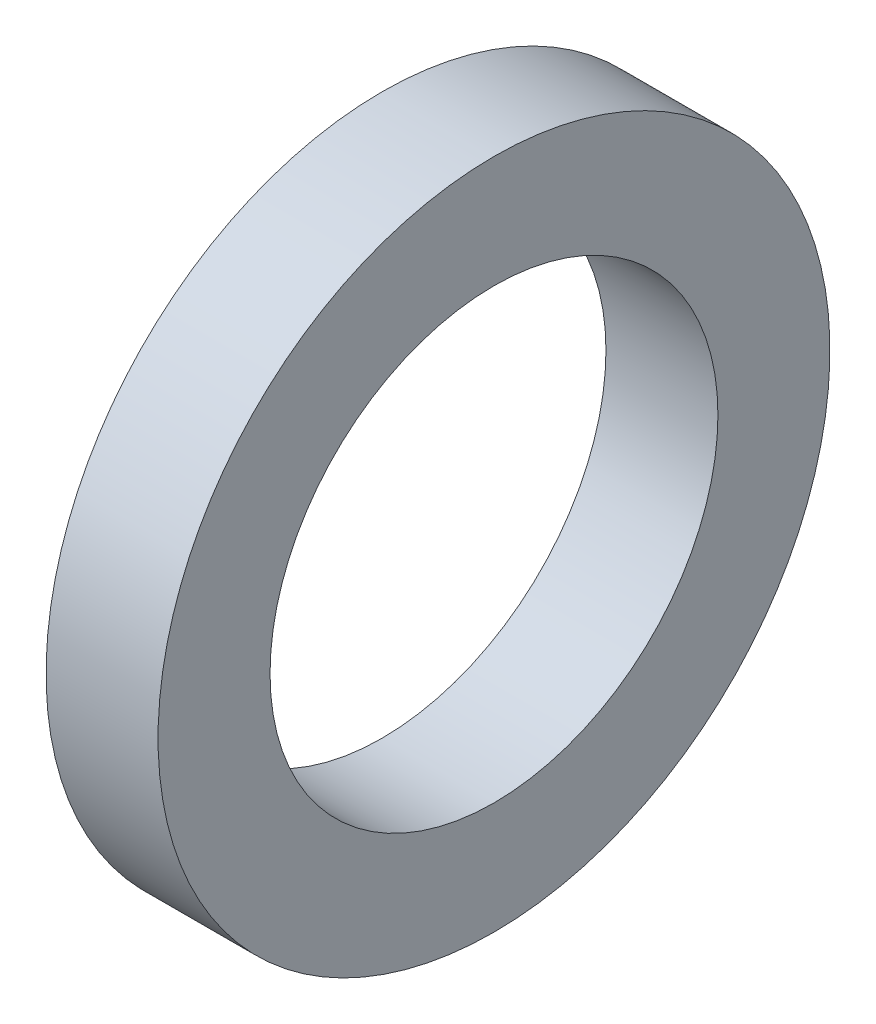
SolidWorks part; units mm, degrees
material "Rubber"
ref_plane "Front Plane" through (0, 0, 0) normal (0, 0, 1) x (1, 0, 0)
ref_plane "Top Plane" through (0, 0, 0) normal (0, 1, 0) x (1, 0, 0)
ref_plane "Right Plane" through (0, 0, 0) normal (1, 0, 0) x (0, 0, -1)
ref_plane "Plane1" through (0, 0, 0) normal (0, 0, 1) x (1, 0, 0)
sketch "Sketch1" plane through (0, 0, 0) normal (0, 0, 1) x (1, 0, 0)
  line L0 (2, 0) -> (2, -6)
  line L1 (2, -6) -> (0, -6)
  line L2 (0, -6) -> (0, 0)
  line L3 (0, 0) -> (2, 0)
  line L4 (0, 0) -> (2, 0) construction
revolve "Revolve1" add sketch "Sketch1" angle 360 about L4
ref_plane "Plane2" through (0, 0, 0) normal (0, 0, 1) x (1, 0, 0)
sketch "Sketch2" plane through (0, 0, 0) normal (0, 0, 1) x (1, 0, 0)
  line L0 (2, 0) -> (2, -4)
  line L1 (2, -4) -> (0, -4)
  line L2 (0, -4) -> (0, 0)
  line L3 (0, 0) -> (2, 0)
  line L4 (0, 0) -> (2, 0) construction
revolve "Cut-Revolve1" cut sketch "Sketch2" angle 360 about L4
